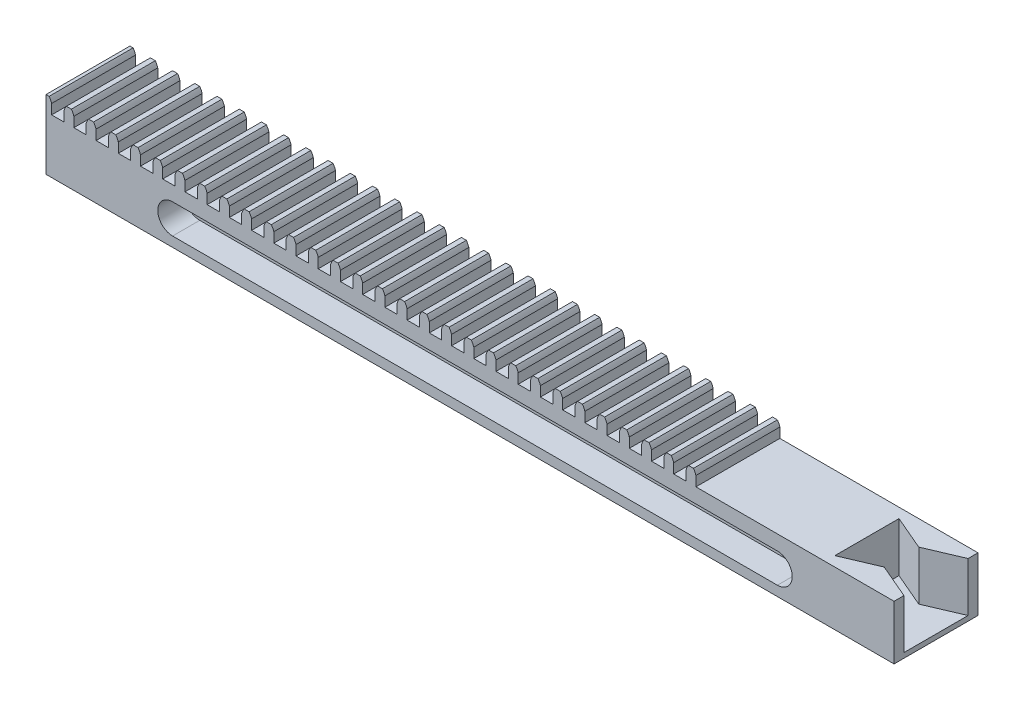
SolidWorks part; units mm, degrees
ref_plane "Front Plane" through (0, 0, 0) normal (0, 0, 1) x (1, 0, 0)
ref_plane "Top Plane" through (0, 0, 0) normal (0, 1, 0) x (1, 0, 0)
ref_plane "Right Plane" through (0, 0, 0) normal (1, 0, 0) x (0, 0, -1)
sketch "Sketch1" plane through (0, 0, 0) normal (0, 0, 1) x (1, 0, 0)
  line L1 (-108.9661, 14.6239) -> (141.0339, 14.6239)
  line L2 (-108.9661, 14.6239) -> (-108.9661, 25.6239)
  line L3 (-108.9661, 25.6239) -> (141.0339, 25.6239)
  line L4 (141.0339, 14.6239) -> (141.0339, 25.6239)
  dimension "D1" = 250
  dimension "D2" = 11
extrude "Boss-Extrude1" add sketch "Sketch1" along normal blind 17
sketch "Sketch2" plane through (0, 0, 0) normal (0, 0, 1) x (1, 0, 0)
  line L1 (-108.9661, 25.6239) -> (-106.9661, 25.6239)
  line L2 (-108.9661, 25.6239) -> (-108.9661, 27.6239)
  line L4 (-106.9661, 25.6239) -> (-106.9661, 27.6239)
  line L5 (-108.4661, 28.6286) -> (-107.4661, 28.6286)
  arc A0 (-108.9661, 27.6239) -> (-108.4661, 28.6286) centre (-105.6232, 26.587) cw
  arc A1 (-106.9661, 27.6239) -> (-107.4661, 28.6286) centre (-110.309, 26.587) ccw
  dimension "D6" = 3.5
  dimension "D7" = 3.5
  dimension "D1" = 2
  dimension "D2" = 2
  dimension "D3" = 1.0047
  dimension "D5" = 1
extrude "Boss-Extrude2" add sketch "Sketch2" along normal blind 17
pattern_linear "LPattern1" count 42 spacing 4.5 along (1, 0, 0) of "Boss-Extrude2"
sketch "Sketch3" plane through (0, 0, 17) normal (0, 0, 1) x (1, 0, 0)
  line L1 (141.0339, 14.6239) -> (141.0339, 25.6239) construction
  line L2 (-28.4661, 19.6239) -> (94.0339, 19.6239) construction
  line L3 (-28.4661, 22.6239) -> (94.0339, 22.6239)
  line L4 (-28.4661, 16.6239) -> (94.0339, 16.6239)
  line L5 (-108.9661, 14.6239) -> (141.0339, 14.6239) construction
  arc A0 (-28.4661, 22.6239) -> (-28.4661, 16.6239) centre (-28.4661, 19.6239) ccw
  arc A1 (94.0339, 16.6239) -> (94.0339, 22.6239) centre (94.0339, 19.6239) ccw
  point P2 (32.7839, 19.6239)
  dimension "D1" = 5
  dimension "D3" = 3
  dimension "D2" = 122.5
  dimension "D4" = 47
extrude "Cut-Extrude1" cut sketch "Sketch3" against normal blind 20
sketch "Sketch4" plane through (0, 25.6239, 0) normal (0, 1, 0) x (1, 0, 0)
  line L0 (-117.5393, -8.5) -> (-83.9872, -8.5) construction
  line L1 (-104.4661, -17) -> (-106.9661, -17) construction
  line L2 (-108.9661, -17) -> (-108.9661, 0) construction
  point P6 (-108.9661, -8.5)
sketch "Sketch5" plane through (0, 0, 17) normal (0, 0, 1) x (1, 0, 0)
  line L1 (-110.1349, 4.7541) -> (-54.1043, 4.7541)
  line L2 (-110.1349, 4.7541) -> (-110.1349, 51.8366)
  line L3 (-110.1349, 51.8366) -> (-54.1043, 51.8366)
  line L4 (-54.1043, 4.7541) -> (-54.1043, 51.8366)
extrude "Cut-Extrude3" cut sketch "Sketch5" against normal blind 30 contours L2 L3 L4 L1
sketch "Sketch11" plane through (0, 14.6239, 0) normal (0, -1, 0) x (1, 0, 0)
  line L1 (-36.5352, 5.5) -> (123.4648, 5.5)
  line L2 (-36.5352, 5.5) -> (-36.5352, 11.5)
  line L3 (-36.5352, 11.5) -> (123.4648, 11.5)
  line L4 (123.4648, 5.5) -> (123.4648, 11.5)
  line L5 (-54.1043, 0) -> (141.0339, 0) construction
  line L6 (-54.1043, 17) -> (-54.1043, 0) construction
  point P4 (-36.5352, 8.5)
  point P7 (-54.1043, 8.5)
  point P8 (43.4648, 5.5)
  point P11 (43.4648, 0)
  dimension "D1" = 6
  dimension "D2" = 160
extrude "Boss-Extrude5" add sketch "Sketch11" against normal blind 10
sketch "Sketch12" plane through (0, 0, 17) normal (0, 0, 1) x (1, 0, 0)
  line L0 (141.0339, 25.6239) -> (77.5339, 25.6239) construction
  line L1 (141.0339, 14.6239) -> (117.6624, 14.6239)
  line L2 (141.0339, 14.6239) -> (141.0339, 25.6239)
  line L3 (141.0339, 25.6239) -> (117.6624, 25.6239)
  line L4 (117.6624, 14.6239) -> (117.6624, 25.6239)
extrude "Cut-Extrude4" cut sketch "Sketch12" against normal blind 30
sketch "Sketch13" plane through (0, 25.6239, 0) normal (0, 1, 0) x (1, 0, 0)
  line L0 (117.6624, -15) -> (110.6624, -12)
  line L1 (117.6624, 0) -> (117.6624, -17) construction
  line L2 (110.6624, -12) -> (103.6624, -15)
  line L3 (103.6624, -15) -> (103.6624, -2)
  line L4 (103.6624, -2) -> (110.6624, -5)
  line L5 (110.6624, -5) -> (117.6624, -2)
  line L6 (117.6624, -2) -> (117.6624, -15)
  point P9 (117.6624, -8.5)
  point P10 (117.6624, -8.5)
  dimension "D1" = 13
  dimension "D2" = 13
  dimension "D3" = 7
  dimension "D4" = 14
  dimension "D5" = 7
  dimension "D6" = 3
extrude "Cut-Extrude5" cut sketch "Sketch13" against normal blind 10
sketch "Sketch14" plane through (-54.1043, 0, 0) normal (-1, 0, 0) x (0, 0, 1)
  line L0 (0, 28.6286) -> (17, 14.6239) construction
sketch "Sketch15" plane through (103.6624, 0, 0) normal (1, 0, 0) x (0, 0, -1)
  line L0 (-15, 25.6239) -> (-2, 15.6239) construction
equation "\"4.55.00mm\"=5"
